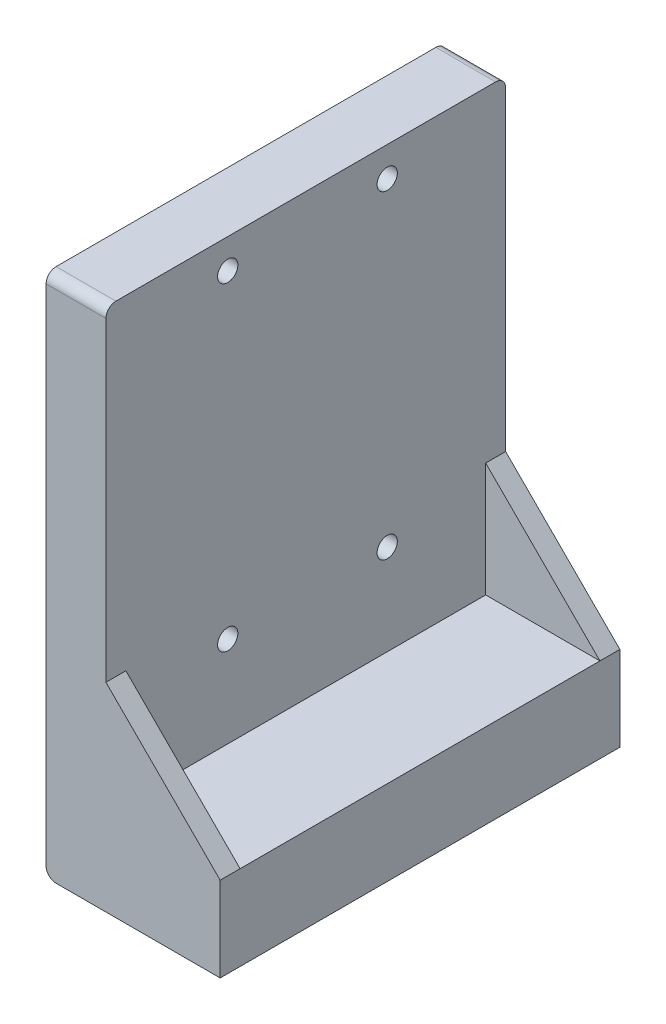
SolidWorks part; units mm, degrees
material "ABS PC"
ref_plane "Front Plane" through (0, 0, 0) normal (0, 0, 1) x (1, 0, 0)
ref_plane "Top Plane" through (0, 0, 0) normal (0, 1, 0) x (1, 0, 0)
ref_plane "Right Plane" through (0, 0, 0) normal (1, 0, 0) x (0, 0, -1)
sketch "Sketch1" plane through (0, 0, 0) normal (0, 0, 1) x (1, 0, 0)
  line L0 (0, 0) -> (0, 52.578)
  line L1 (0, 52.578) -> (6, 52.578)
  line L2 (6, 52.578) -> (6, 8.5)
  line L3 (6, 8.5) -> (76, 8.5)
  line L4 (76, 8.5) -> (76, 0)
  line L5 (76, 0) -> (0, 0)
  dimension "D1" = 52.578
  dimension "D2" = 8.5
  dimension "D3" = 6
  dimension "D4" = 76
extrude "Boss-Extrude1" add sketch "Sketch1" along normal blind 40.1
sketch "Sketch3" plane through (0, 0, 40.1) normal (0, 0, 1) x (1, 0, 0)
  line L0 (0, 52.578) -> (0, 0) construction
  line L1 (0, 0) -> (76, 0) construction
  circle A0 centre (27.996, 2.8) radius 1.35
  circle A1 centre (49.996, 2.8) radius 1.35
  circle A2 centre (71.996, 2.8) radius 1.35
  dimension "D1" = 2.7
  dimension "D4" = 2.7
  dimension "D5" = 2.7
  dimension "D2" = 27.996
  dimension "D3" = 2.8
  dimension "D6" = 22
  dimension "D7" = 22
extrude "Cut-Extrude2" cut sketch "Sketch3" against normal blind 50.8
sketch "Sketch4" plane through (0, 0, 0) normal (-1, 0, 0) x (0, 0, 1)
  line L0 (40.1, 0) -> (0, 0) construction
  line L1 (20.05, 0) -> (20.05, 52.578) construction
  line L2 (40.1, 52.578) -> (0, 52.578) construction
  line L3 (40.1, 52.578) -> (40.1, 0) construction
  line L5 (0, 52.578) -> (0, 0) construction
  circle A0 centre (27.88, 17.6) radius 1.016
  circle A1 centre (11.88, 17.6) radius 1.016
  circle A2 centre (27.88, 49.6) radius 1.016
  circle A3 centre (11.88, 49.6) radius 1.016
  dimension "D1" = 2.032
  dimension "D3" = 2.032
  dimension "D4" = 2.978
  dimension "D2" = 17.6
  dimension "D5" = 12.22
  dimension "D6" = 12.22
  dimension "D7" = 11.88
  dimension "D8" = 11.88
  dimension "D9" = 2.978
extrude "Cut-Extrude3" cut sketch "Sketch4" against normal blind 50.8
sketch "Sketch6" plane through (0, 0, 0) normal (0, -1, 0) x (1, 0, 0)
  line L0 (0, 40.1) -> (76, 40.1) construction
  line L1 (19, 37.1) -> (81.0861, 37.1)
  line L2 (19, 37.1) -> (19, 3)
  line L3 (19, 3) -> (81.0861, 3)
  line L4 (81.0861, 37.1) -> (81.0861, 3)
  line L5 (0, 0) -> (76, 0) construction
  line L6 (0, 40.1) -> (0, 0) construction
  dimension "D1" = 3
  dimension "D2" = 3
  dimension "D3" = 19
extrude "Cut-Extrude4" cut sketch "Sketch6" against normal blind 6
ref_plane "Plane5" through (0, 0, 20.05) normal (0, 0, -1) x (-1, 0, 0)
sketch "Sketch16" plane through (0, 0, 40.1) normal (0, 0, 1) x (1, 0, 0)
  line L0 (6, 8.5) -> (26, 8.5)
  line L1 (76, 8.5) -> (6, 8.5) construction
  line L2 (26, 8.5) -> (6, 33.5)
  line L3 (6, 8.5) -> (6, 52.578) construction
  line L4 (6, 33.5) -> (6, 8.5)
  dimension "D1" = 20
  dimension "D2" = 25
extrude "Boss-Extrude5" add sketch "Sketch16" against normal blind 2
mirror "Mirror2" about plane through (0, 0, 20.05) normal (0, 0, -1) of "Boss-Extrude5"
fillet "Fillet1" radius 1 5 edges at (3, 52.578, 40.1) (3, 52.578, 0) (0, 0, 20.05) (76, 0, 1.5) (76, 0, 38.6)
sketch "Sketch17" plane through (0, 0, 40.1) normal (0, 0, 1) x (1, 0, 0)
  line L0 (17.4625, 0) -> (17.4625, 8.5)
  line L1 (17.4625, 8.5) -> (6, 19.9625)
  line L2 (6, 19.9625) -> (6, 33.5)
  line L7 (6, 33.5) -> (6, 51.578)
  line L8 (6, 51.578) -> (0, 51.578)
  line L9 (0, 51.578) -> (0, 1)
  line L10 (1, 0) -> (75, 0)
  line L11 (76, 1) -> (76, 8.5)
  line L12 (76, 8.5) -> (26, 8.5)
  line L13 (26, 8.5) -> (6, 33.5)
  line L17 (17.4625, 0) -> (75, 0)
  line L18 (76, 1) -> (76, 8.5)
  line L19 (76, 8.5) -> (26, 8.5)
  line L20 (26, 8.5) -> (6, 33.5)
  arc A2 (0, 1) -> (1, 0) centre (1, 1) ccw
  arc A3 (75, 0) -> (76, 1) centre (75, 1) ccw
  arc A5 (75, 0) -> (76, 1) centre (75, 1) ccw
  dimension "D2" = 58.5375
  dimension "D1" = 0
extrude "Cut-Extrude5" cut sketch "Sketch17" against normal through all
